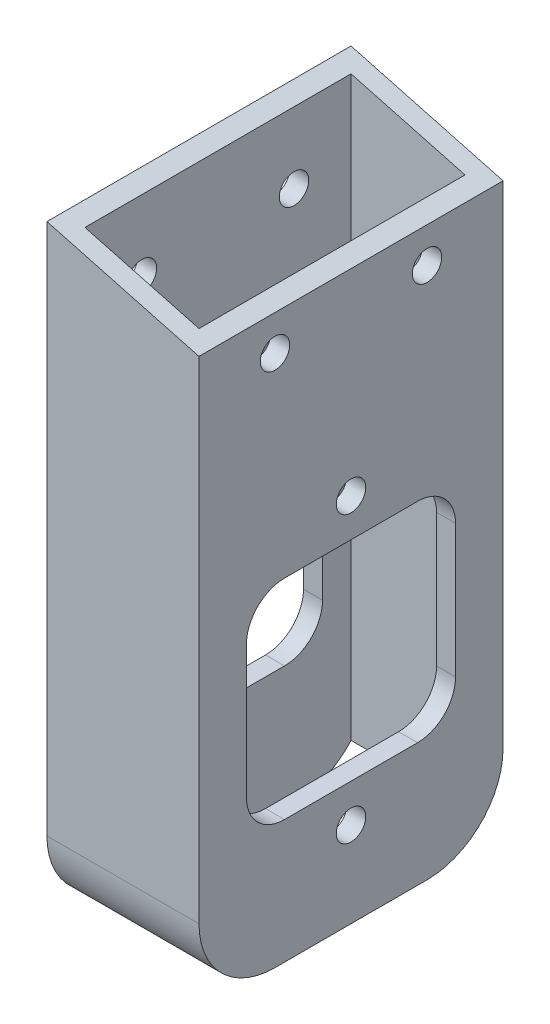
SolidWorks part; units mm, degrees
ref_plane "Front" through (0, 0, 0) normal (0, 0, 1) x (1, 0, 0)
ref_plane "Top" through (0, 0, 0) normal (0, 1, 0) x (1, 0, 0)
ref_plane "Right" through (0, 0, 0) normal (1, 0, 0) x (0, 0, -1)
sketch "Sketch1" plane through (0, 0, 0) normal (0, 1, 0) x (1, 0, 0)
  line L0 (-9.525, 22.225) -> (-9.525, -22.225)
  line L1 (-12.7, 25.4) -> (12.7, 25.4)
  line L2 (-12.7, 25.4) -> (-12.7, -25.4)
  line L3 (-12.7, -25.4) -> (12.7, -25.4)
  line L4 (12.7, 25.4) -> (12.7, -25.4)
  line L5 (-12.7, 25.4) -> (12.7, -25.4) construction
  line L6 (-12.7, -25.4) -> (12.7, 25.4) construction
  line L7 (-9.525, -22.225) -> (9.525, -22.225)
  line L8 (9.525, 22.225) -> (9.525, -22.225)
  line L9 (-9.525, 22.225) -> (9.525, 22.225)
  point P0 (0, 0)
  dimension "D2" = 25.4
  dimension "D3" = 50.8
  dimension "D1" = 3.175
extrude "Boss-Extrude1" add sketch "Sketch1" along normal blind 101.6
sketch "Sketch2" plane through (0, 0, 25.4) normal (0, 0, 1) x (1, 0, 0)
  line L0 (-12.7, 101.6) -> (12.7, 94.7941)
  line L1 (12.7, 101.6) -> (12.7, 0) construction
  line L6 (-12.7, 0) -> (12.7, 0)
  line L7 (12.7, 0) -> (12.7, 101.6)
  line L8 (12.7, 101.6) -> (-12.7, 101.6)
  line L9 (-12.7, 101.6) -> (-12.7, 0)
  line L10 (-12.7, 0) -> (12.7, 0)
  line L11 (12.7, 0) -> (12.7, 101.6)
  line L12 (12.7, 101.6) -> (-12.7, 101.6)
  line L13 (-12.7, 101.6) -> (-12.7, 0)
  line M7 (12.7, 0) -> (12.7, 101.6)
  line M8 (12.7, 101.6) -> (-12.7, 101.6)
  dimension "D2" = 15
  dimension "D1" = 0
extrude "Cut-Extrude1" cut sketch "Sketch2" against normal through all contours L0 M8 M7
sketch "Sketch3" plane through (-12.7, 0, 0) normal (-1, 0, 0) x (0, 0, 1)
  line L4 (-25.4, 0) -> (25.4, 0)
  line L5 (25.4, 0) -> (25.4, 101.6)
  line L6 (25.4, 101.6) -> (-25.4, 101.6)
  line L7 (-25.4, 101.6) -> (-25.4, 0)
  line L8 (-12.7, 0) -> (12.7, 0)
  line L9 (25.4, 12.7) -> (25.4, 101.6)
  line L10 (25.4, 101.6) -> (-25.4, 101.6)
  line L11 (-25.4, 101.6) -> (-25.4, 12.7)
  arc A0 (12.7, 0) -> (25.4, 12.7) centre (12.7, 12.7) ccw
  arc A1 (-12.7, 0) -> (-25.4, 12.7) centre (-12.7, 12.7) cw
  line M7 (-25.4, 0) -> (25.4, 0)
  line M8 (25.4, 0) -> (25.4, 101.6)
  line M10 (-25.4, 101.6) -> (-25.4, 0)
  dimension "D2" = 12.7
  dimension "D1" = 0
extrude "Cut-Extrude2" cut sketch "Sketch3" against normal through all contours A1 M7 M10 | A0 M7 M8
sketch "Sketch4" plane through (-12.7, 0, 0) normal (-1, 0, 0) x (0, 0, 1)
  line L0 (0, 0) -> (0, 38.1) construction
  line L1 (-12.7, 0) -> (12.7, 0) construction
  line L2 (17.4625, 55.5625) -> (-17.4625, 55.5625)
  line L3 (17.4625, 55.5625) -> (17.4625, 20.6375)
  line L4 (17.4625, 20.6375) -> (-17.4625, 20.6375)
  line L5 (-17.4625, 55.5625) -> (-17.4625, 20.6375)
  line L6 (17.4625, 55.5625) -> (-17.4625, 20.6375) construction
  line L7 (17.4625, 20.6375) -> (-17.4625, 55.5625) construction
  point P6 (0, 0)
  dimension "D1" = 34.925
  dimension "D2" = 38.1
extrude "Cut-Extrude3" cut sketch "Sketch4" against normal through all
hole_wizard "#10 (0.1935) Diameter Hole1" positions "Sketch7" profile "Sketch6" hole size "#10" standard "ANSI Inch" end condition through all
sketch "Sketch7" plane through (-12.7, 0, 0) normal (-1, 0, 0) x (0, 0, 1)
  line L0 (0, 61.9125) -> (0, 14.2875) construction
  circle A0 centre (0, 38.1) radius 23.8125 construction
  point P0 (0, 61.9125)
  point P2 (0, 14.2875)
  point P15 (0, 38.1)
  dimension "D1" = 47.625
sketch "Sketch6" plane through (-12.7, 61.9125, 0) normal (0, 1, 0) x (0, 0, 1)
  line L0 (0, 0) -> (0, 25.4)
  line L1 (0, 25.4) -> (2.4574, 25.4)
  line L2 (2.4574, 25.4) -> (2.4574, 0)
  line L5 (2.4574, 0) -> (0, 0)
  line L11 (0, -6.35) -> (0, 107.95) construction
  dimension "Thru Hole Dia." = 4.9149
  dimension "Thru Hole Depth" = 25.4
fillet "Fillet1" radius 6.35 8 edges at (11.1125, 55.5625, 17.4625) (11.1125, 20.6375, -17.4625) (11.1125, 55.5625, -17.4625) (11.1125, 20.6375, 17.4625) (-11.1125, 55.5625, -17.4625) (-11.1125, 55.5625, 17.4625) (-11.1125, 20.6375, -17.4625) (-11.1125, 20.6375, 17.4625)
hole_wizard "#10 (0.1935) Diameter Hole2" positions "Sketch8" profile "Sketch9" hole size "#10" standard "ANSI Inch" end condition through all
sketch "Sketch8" plane through (-12.7, 0, 0) normal (-1, 0, 0) x (0, 0, 1)
  line L0 (-25.4, 88.9) -> (-12.7, 88.9) construction
  line L1 (-25.4, 101.6) -> (-25.4, 12.7) construction
  line L3 (0, 101.6) -> (0, 84.9315) construction
  line L4 (-25.4, 101.6) -> (25.4, 101.6) construction
  point P0 (-12.7, 88.9)
  point P13 (1.3913, 84.9897)
  point P14 (0, 0)
  point P15 (12.7, 88.9)
  dimension "D1" = 25.4
  dimension "D2" = 12.7
sketch "Sketch9" plane through (-12.7, 88.9, -12.7) normal (0, 1, 0) x (0, 0, 1)
  line L0 (0, 0) -> (0, 25.4)
  line L1 (0, 25.4) -> (2.4574, 25.4)
  line L2 (2.4574, 25.4) -> (2.4574, 0)
  line L5 (2.4574, 0) -> (0, 0)
  line L11 (0, -6.35) -> (0, 107.95) construction
  dimension "Thru Hole Dia." = 4.9149
  dimension "Thru Hole Depth" = 25.4
